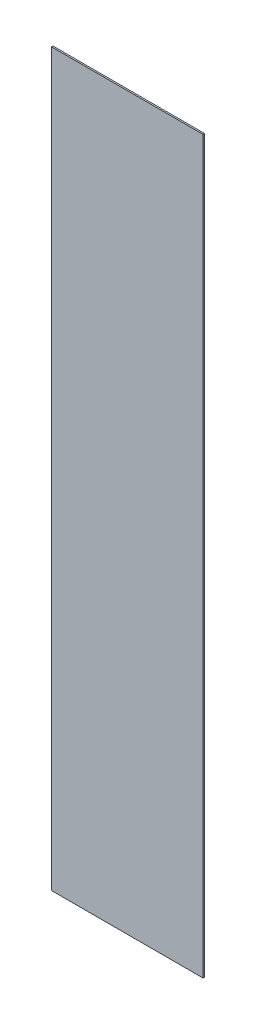
SolidWorks part; units mm, degrees
ref_plane "Front Plane" through (0, 0, 0) normal (0, 0, 1) x (1, 0, 0)
ref_plane "Top Plane" through (0, 0, 0) normal (0, 1, 0) x (1, 0, 0)
ref_plane "Right Plane" through (0, 0, 0) normal (1, 0, 0) x (0, 0, -1)
sketch "Sketch1" plane through (0, 0, 0) normal (0, 0, 1) x (1, 0, 0)
  line L1 (500, -2412.525) -> (-500, -2412.525)
  line L2 (500, -2412.525) -> (500, 2412.525)
  line L3 (500, 2412.525) -> (-500, 2412.525)
  line L4 (-500, -2412.525) -> (-500, 2412.525)
  line L5 (500, -2412.525) -> (-500, 2412.525) construction
  line L6 (500, 2412.525) -> (-500, -2412.525) construction
  point P0 (0, 0)
extrude "Boss-Extrude1" add sketch "Sketch1" along normal blind 10
